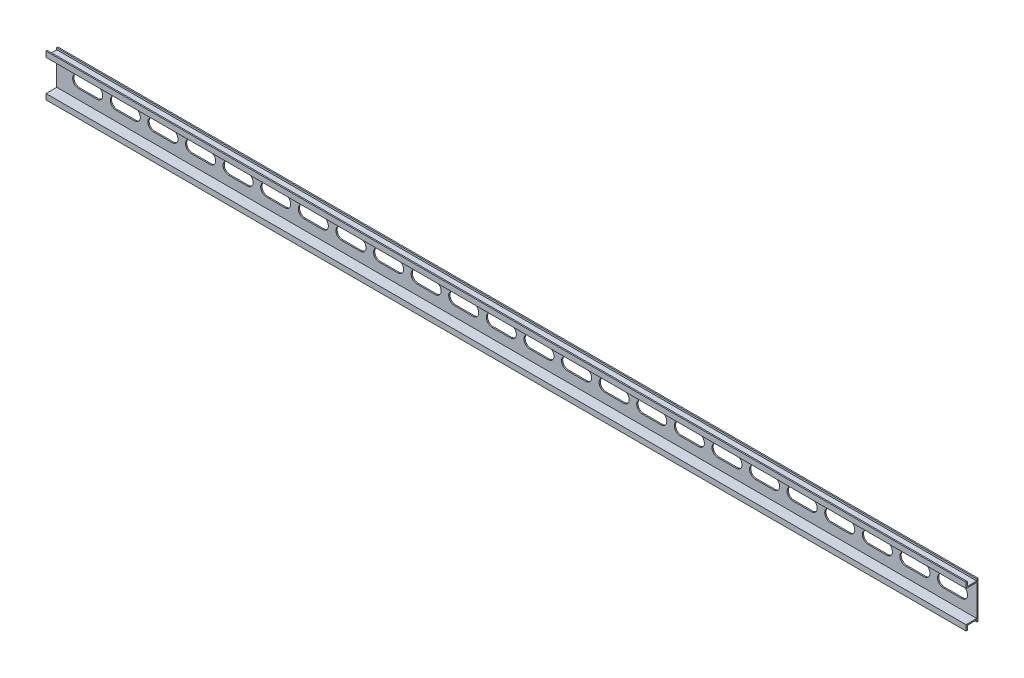
SolidWorks part; units mm, degrees
ref_plane "Front Plane" through (0, 0, 0) normal (0, 0, 1) x (1, 0, 0)
ref_plane "Top Plane" through (0, 0, 0) normal (0, 1, 0) x (1, 0, 0)
ref_plane "Right Plane" through (0, 0, 0) normal (1, 0, 0) x (0, 0, -1)
sketch "Sketch1" plane through (0, 0, 0) normal (1, 0, 0) x (0, 0, -1)
  line L0 (0, 0) -> (96.2341, 0) construction
  line L1 (0, 12.954) -> (0, -12.954)
  line L2 (0, -12.954) -> (-8.89, -12.954)
  line L3 (-8.89, -12.954) -> (-8.89, -17.526)
  line L4 (-8.89, -17.526) -> (-7.874, -17.526)
  line L5 (-7.874, -17.526) -> (-7.874, -13.97)
  line L6 (-7.874, -13.97) -> (0, -13.97)
  line L7 (0, -13.97) -> (0, -15.494)
  line L8 (0, -15.494) -> (1.016, -15.494)
  line L9 (1.016, -15.494) -> (1.016, 15.494)
  line L10 (-7.874, 17.526) -> (-7.874, 13.97)
  line L11 (-8.89, 17.526) -> (-7.874, 17.526)
  line L12 (-8.89, 12.954) -> (-8.89, 17.526)
  line L13 (0, 12.954) -> (-8.89, 12.954)
  line L14 (-7.874, 13.97) -> (0, 13.97)
  line L15 (0, 15.494) -> (1.016, 15.494)
  line L16 (0, 13.97) -> (0, 15.494)
  point P20 (1.016, 0)
  dimension "D1" = 96.2341
  dimension "D2" = 25.908
  dimension "D3" = 9.906
  dimension "D4" = 1.016
  dimension "D5" = 1.016
  dimension "D6" = 1.016
  dimension "D7" = 30.988
  dimension "D8" = 1.016
  dimension "D9" = 35.052
extrude "Boss-Extrude1" add sketch "Sketch1" along normal blind 762
sketch "Sketch2" plane through (0, 0, -1.016) normal (0, 0, -1) x (-1, 0, 0)
  line L0 (-749.554, 0) -> (-734.314, 0) construction
  line L1 (-749.554, 4.826) -> (-734.314, 4.826)
  line L2 (-749.554, -4.826) -> (-734.314, -4.826)
  line L3 (-762, -15.494) -> (-762, 15.494) construction
  line L4 (-718.4114, 0) -> (-703.1714, 0) construction
  line L5 (-718.4114, 4.826) -> (-703.1714, 4.826)
  line L6 (-718.4114, -4.826) -> (-703.1714, -4.826)
  line L7 (-687.2688, 0) -> (-672.0288, 0) construction
  line L8 (-687.2688, 4.826) -> (-672.0288, 4.826)
  line L9 (-687.2688, -4.826) -> (-672.0288, -4.826)
  line L10 (-656.1262, 0) -> (-640.8862, 0) construction
  line L11 (-656.1262, 4.826) -> (-640.8862, 4.826)
  line L12 (-656.1262, -4.826) -> (-640.8862, -4.826)
  line L13 (-624.9836, 0) -> (-609.7436, 0) construction
  line L14 (-624.9836, 4.826) -> (-609.7436, 4.826)
  line L15 (-624.9836, -4.826) -> (-609.7436, -4.826)
  line L16 (-593.841, 0) -> (-578.601, 0) construction
  line L17 (-593.841, 4.826) -> (-578.601, 4.826)
  line L18 (-593.841, -4.826) -> (-578.601, -4.826)
  line L19 (-562.6983, 0) -> (-547.4583, 0) construction
  line L20 (-562.6983, 4.826) -> (-547.4583, 4.826)
  line L21 (-562.6983, -4.826) -> (-547.4583, -4.826)
  line L22 (-531.5557, 0) -> (-516.3157, 0) construction
  line L23 (-531.5557, 4.826) -> (-516.3157, 4.826)
  line L24 (-531.5557, -4.826) -> (-516.3157, -4.826)
  line L25 (-500.4131, 0) -> (-485.1731, 0) construction
  line L26 (-500.4131, 4.826) -> (-485.1731, 4.826)
  line L27 (-500.4131, -4.826) -> (-485.1731, -4.826)
  line L28 (-469.2705, 0) -> (-454.0305, 0) construction
  line L29 (-469.2705, 4.826) -> (-454.0305, 4.826)
  line L30 (-469.2705, -4.826) -> (-454.0305, -4.826)
  line L31 (-438.1279, 0) -> (-422.8879, 0) construction
  line L32 (-438.1279, 4.826) -> (-422.8879, 4.826)
  line L33 (-438.1279, -4.826) -> (-422.8879, -4.826)
  line L34 (-406.9853, 0) -> (-391.7453, 0) construction
  line L35 (-406.9853, 4.826) -> (-391.7453, 4.826)
  line L36 (-406.9853, -4.826) -> (-391.7453, -4.826)
  line L37 (-375.8427, 0) -> (-360.6027, 0) construction
  line L38 (-375.8427, 4.826) -> (-360.6027, 4.826)
  line L39 (-375.8427, -4.826) -> (-360.6027, -4.826)
  line L40 (-344.7001, 0) -> (-329.4601, 0) construction
  line L41 (-344.7001, 4.826) -> (-329.4601, 4.826)
  line L42 (-344.7001, -4.826) -> (-329.4601, -4.826)
  line L43 (-313.5575, 0) -> (-298.3175, 0) construction
  line L44 (-313.5575, 4.826) -> (-298.3175, 4.826)
  line L45 (-313.5575, -4.826) -> (-298.3175, -4.826)
  line L46 (-282.4149, 0) -> (-267.1749, 0) construction
  line L47 (-282.4149, 4.826) -> (-267.1749, 4.826)
  line L48 (-282.4149, -4.826) -> (-267.1749, -4.826)
  line L49 (-251.2723, 0) -> (-236.0323, 0) construction
  line L50 (-251.2723, 4.826) -> (-236.0323, 4.826)
  line L51 (-251.2723, -4.826) -> (-236.0323, -4.826)
  line L52 (-220.1297, 0) -> (-204.8897, 0) construction
  line L53 (-220.1297, 4.826) -> (-204.8897, 4.826)
  line L54 (-220.1297, -4.826) -> (-204.8897, -4.826)
  line L55 (-188.987, 0) -> (-173.747, 0) construction
  line L56 (-188.987, 4.826) -> (-173.747, 4.826)
  line L57 (-188.987, -4.826) -> (-173.747, -4.826)
  line L58 (-157.8444, 0) -> (-142.6044, 0) construction
  line L59 (-157.8444, 4.826) -> (-142.6044, 4.826)
  line L60 (-157.8444, -4.826) -> (-142.6044, -4.826)
  line L61 (-126.7018, 0) -> (-111.4618, 0) construction
  line L62 (-126.7018, 4.826) -> (-111.4618, 4.826)
  line L63 (-126.7018, -4.826) -> (-111.4618, -4.826)
  line L64 (-95.5592, 0) -> (-80.3192, 0) construction
  line L65 (-95.5592, 4.826) -> (-80.3192, 4.826)
  line L66 (-95.5592, -4.826) -> (-80.3192, -4.826)
  line L67 (-64.4166, 0) -> (-49.1766, 0) construction
  line L68 (-64.4166, 4.826) -> (-49.1766, 4.826)
  line L69 (-64.4166, -4.826) -> (-49.1766, -4.826)
  line L70 (-33.274, 0) -> (-18.034, 0) construction
  line L71 (-33.274, 4.826) -> (-18.034, 4.826)
  line L72 (-33.274, -4.826) -> (-18.034, -4.826)
  line L73 (0, -15.494) -> (0, 15.494) construction
  arc A0 (-749.554, 4.826) -> (-749.554, -4.826) centre (-749.554, 0) ccw
  arc A1 (-734.314, -4.826) -> (-734.314, 4.826) centre (-734.314, 0) ccw
  arc A2 (-718.4114, 4.826) -> (-718.4114, -4.826) centre (-718.4114, 0) ccw
  arc A3 (-703.1714, -4.826) -> (-703.1714, 4.826) centre (-703.1714, 0) ccw
  arc A4 (-687.2688, 4.826) -> (-687.2688, -4.826) centre (-687.2688, 0) ccw
  arc A5 (-672.0288, -4.826) -> (-672.0288, 4.826) centre (-672.0288, 0) ccw
  arc A6 (-656.1262, 4.826) -> (-656.1262, -4.826) centre (-656.1262, 0) ccw
  arc A7 (-640.8862, -4.826) -> (-640.8862, 4.826) centre (-640.8862, 0) ccw
  arc A8 (-624.9836, 4.826) -> (-624.9836, -4.826) centre (-624.9836, 0) ccw
  arc A9 (-609.7436, -4.826) -> (-609.7436, 4.826) centre (-609.7436, 0) ccw
  arc A10 (-593.841, 4.826) -> (-593.841, -4.826) centre (-593.841, 0) ccw
  arc A11 (-578.601, -4.826) -> (-578.601, 4.826) centre (-578.601, 0) ccw
  arc A12 (-562.6983, 4.826) -> (-562.6983, -4.826) centre (-562.6983, 0) ccw
  arc A13 (-547.4583, -4.826) -> (-547.4583, 4.826) centre (-547.4583, 0) ccw
  arc A14 (-531.5557, 4.826) -> (-531.5557, -4.826) centre (-531.5557, 0) ccw
  arc A15 (-516.3157, -4.826) -> (-516.3157, 4.826) centre (-516.3157, 0) ccw
  arc A16 (-500.4131, 4.826) -> (-500.4131, -4.826) centre (-500.4131, 0) ccw
  arc A17 (-485.1731, -4.826) -> (-485.1731, 4.826) centre (-485.1731, 0) ccw
  arc A18 (-469.2705, 4.826) -> (-469.2705, -4.826) centre (-469.2705, 0) ccw
  arc A19 (-454.0305, -4.826) -> (-454.0305, 4.826) centre (-454.0305, 0) ccw
  arc A20 (-438.1279, 4.826) -> (-438.1279, -4.826) centre (-438.1279, 0) ccw
  arc A21 (-422.8879, -4.826) -> (-422.8879, 4.826) centre (-422.8879, 0) ccw
  arc A22 (-406.9853, 4.826) -> (-406.9853, -4.826) centre (-406.9853, 0) ccw
  arc A23 (-391.7453, -4.826) -> (-391.7453, 4.826) centre (-391.7453, 0) ccw
  arc A24 (-375.8427, 4.826) -> (-375.8427, -4.826) centre (-375.8427, 0) ccw
  arc A25 (-360.6027, -4.826) -> (-360.6027, 4.826) centre (-360.6027, 0) ccw
  arc A26 (-344.7001, 4.826) -> (-344.7001, -4.826) centre (-344.7001, 0) ccw
  arc A27 (-329.4601, -4.826) -> (-329.4601, 4.826) centre (-329.4601, 0) ccw
  arc A28 (-313.5575, 4.826) -> (-313.5575, -4.826) centre (-313.5575, 0) ccw
  arc A29 (-298.3175, -4.826) -> (-298.3175, 4.826) centre (-298.3175, 0) ccw
  arc A30 (-282.4149, 4.826) -> (-282.4149, -4.826) centre (-282.4149, 0) ccw
  arc A31 (-267.1749, -4.826) -> (-267.1749, 4.826) centre (-267.1749, 0) ccw
  arc A32 (-251.2723, 4.826) -> (-251.2723, -4.826) centre (-251.2723, 0) ccw
  arc A33 (-236.0323, -4.826) -> (-236.0323, 4.826) centre (-236.0323, 0) ccw
  arc A34 (-220.1297, 4.826) -> (-220.1297, -4.826) centre (-220.1297, 0) ccw
  arc A35 (-204.8897, -4.826) -> (-204.8897, 4.826) centre (-204.8897, 0) ccw
  arc A36 (-188.987, 4.826) -> (-188.987, -4.826) centre (-188.987, 0) ccw
  arc A37 (-173.747, -4.826) -> (-173.747, 4.826) centre (-173.747, 0) ccw
  arc A38 (-157.8444, 4.826) -> (-157.8444, -4.826) centre (-157.8444, 0) ccw
  arc A39 (-142.6044, -4.826) -> (-142.6044, 4.826) centre (-142.6044, 0) ccw
  arc A40 (-126.7018, 4.826) -> (-126.7018, -4.826) centre (-126.7018, 0) ccw
  arc A41 (-111.4618, -4.826) -> (-111.4618, 4.826) centre (-111.4618, 0) ccw
  arc A42 (-95.5592, 4.826) -> (-95.5592, -4.826) centre (-95.5592, 0) ccw
  arc A43 (-80.3192, -4.826) -> (-80.3192, 4.826) centre (-80.3192, 0) ccw
  arc A44 (-64.4166, 4.826) -> (-64.4166, -4.826) centre (-64.4166, 0) ccw
  arc A45 (-49.1766, -4.826) -> (-49.1766, 4.826) centre (-49.1766, 0) ccw
  arc A46 (-33.274, 4.826) -> (-33.274, -4.826) centre (-33.274, 0) ccw
  arc A47 (-18.034, -4.826) -> (-18.034, 4.826) centre (-18.034, 0) ccw
  point P3 (-741.934, 0)
  point P10 (-754.38, 0)
  point P11 (-729.488, 0)
  point P16 (-710.7914, 0)
  point P23 (-679.6488, 0)
  point P30 (-648.5062, 0)
  point P37 (-617.3636, 0)
  point P44 (-586.221, 0)
  point P51 (-555.0783, 0)
  point P58 (-523.9357, 0)
  point P65 (-492.7931, 0)
  point P72 (-461.6505, 0)
  point P79 (-430.5079, 0)
  point P86 (-399.3653, 0)
  point P93 (-368.2227, 0)
  point P100 (-337.0801, 0)
  point P107 (-305.9375, 0)
  point P114 (-274.7949, 0)
  point P121 (-243.6523, 0)
  point P128 (-212.5097, 0)
  point P135 (-181.367, 0)
  point P142 (-150.2244, 0)
  point P149 (-119.0818, 0)
  point P156 (-87.9392, 0)
  point P163 (-56.7966, 0)
  point P170 (-25.654, 0)
  dimension "D1" = 4.826
  dimension "D2" = 24.892
  dimension "D3" = 20.066
  dimension "D4" = 18.034
extrude "Cut-Extrude1" cut sketch "Sketch2" against normal through all
